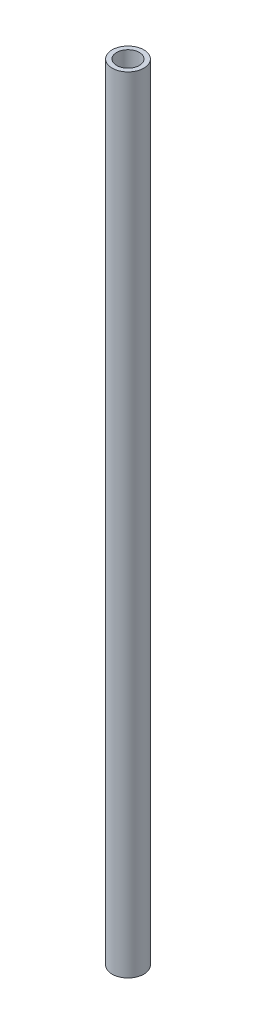
SolidWorks part; units mm, degrees
ref_plane "Plan de face" through (0, 0, 0) normal (0, 0, 1) x (1, 0, 0)
ref_plane "Plan de dessus" through (0, 0, 0) normal (0, 1, 0) x (1, 0, 0)
ref_plane "Plan de droite" through (0, 0, 0) normal (1, 0, 0) x (0, 0, -1)
sketch "Esquisse1" plane through (0, 0, 0) normal (0, 1, 0) x (1, 0, 0)
  circle A0 centre (0, 0) radius 3.5
  circle A1 centre (0, 0) radius 2.5
  dimension "D1" = 7
  dimension "D2" = 1
extrude "Boss.-Extru.1" add sketch "Esquisse1" along normal blind 173
